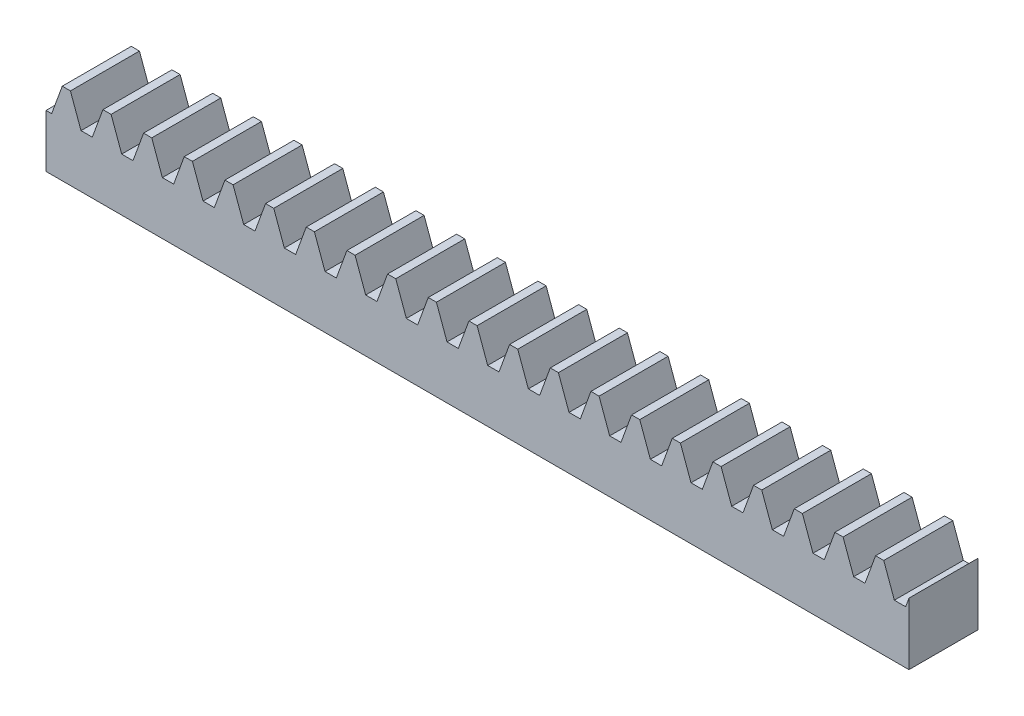
SolidWorks part; units mm, degrees
extrude "Blank" add sketch "BlankSke" against normal blind 8
sketch "BlankSke" plane through (0, 0, 0) normal (0, 0, 1) x (1, 0, 0)
  line L1 (0, 0) -> (100, 0)
  line L2 (0, 0) -> (0, 9.5)
  line L3 (0, 9.5) -> (100, 9.5)
  line L4 (100, 0) -> (100, 9.5)
  dimension "Length" = 100
  dimension "Blank_height" = 9.5
material "ABS PC"
ref_plane "Plane1" through (0, 0, 0) normal (0, 0, 1) x (1, 0, 0)
ref_plane "Plane2" through (0, 0, 0) normal (0, 1, 0) x (1, 0, 0)
ref_plane "Plane3" through (0, 0, 0) normal (1, 0, 0) x (0, 0, -1)
sketch "HoldingSke" plane through (0, 0, 0) normal (0, 1, 0) x (1, 0, 0)
  line L0 (0, 0) -> (0.0928, 0.6602)
  line L1 (-15, 0) -> (100, 0) construction
  line L2 (0, 0) -> (-2.1039, 2.3779)
  line L3 (0, 0) -> (-11.863, 4.5341)
  line L4 (0, 0) -> (7.9495, 3.3743)
  line L5 (0, 0) -> (-23.7986, -8.8762)
  line L6 (0, 0) -> (-10.5278, -7.1032)
  line L9 (-71.009, 38.7566) -> (22.9603, 72.9586)
  line L10 (-76.2, 3.8779) -> (-68.2, 3.8779)
  line L11 (0, 0) -> (-8, 0)
  line L12 (-76.2, 101.6) -> (-76.147, 101.6)
  line L13 (24.9733, 27.94) -> (52.9518, 28.4284)
  line L14 (24.9733, 27.94) -> (24.9743, 27.94)
  line L15 (24.9733, 27.94) -> (100.4006, 29.5858)
  circle A0 centre (0, 0) radius 19.05
  circle A1 centre (0, 0) radius 4
  circle A2 centre (0, 0) radius 12.7
  dimension "MPH" = 8
  dimension "Diameter" = 38.1
  dimension "Num_teeth" = 23
  dimension "Pitch" = 0.6667
  dimension "Show_teeth" = 998
  dimension "Thickness" = 12.7
  dimension "Ap" = 20
  dimension "Pitch_height" = 8
  dimension "Width" = 8
  dimension "Backlash" = 0.053
  dimension "Addendum_fac" = 1
  dimension "Dedendum_fac" = 1.25
  dimension "Clearance_fac" = 0.25
  dimension "Dedendum_add" = 0.001
  dimension "Length" = 100
  dimension "Module" = 1.5
sketch "TooCutSkeIll" plane through (0, 0, 0) normal (0, 0, 1) x (1, 0, 0)
  line L0 (-1.8687, 9.4605) -> (-0.7447, 6.3724)
  line L1 (-0.3914, 6.125) -> (0.3914, 6.125)
  line L2 (0.7447, 6.3724) -> (1.8687, 9.4605)
  line L3 (100, 9.5) -> (0, 9.5) construction
  line L4 (0, 0) -> (0, 64.897) construction
  line L5 (-13.208, 8) -> (12.954, 8) construction
  line L6 (0, 0) -> (100, 0) construction
  line L7 (1.3371, 8) -> (1.3371, 48.7463) construction
  line L8 (-1.3371, 8) -> (-1.3371, 48.7463) construction
  line L9 (1.9251, 9.5) -> (1.9251, 9.5254)
  line L10 (-1.9251, 9.5) -> (-1.9251, 9.5254)
  line L11 (-1.9251, 9.5254) -> (1.9251, 9.5254)
  arc A0 (0.3914, 6.125) -> (0.7447, 6.3724) centre (0.3914, 6.501) ccw
  arc A1 (-0.7447, 6.3724) -> (-0.3914, 6.125) centre (-0.3914, 6.501) ccw
  arc A2 (1.9251, 9.5) -> (1.8687, 9.4605) centre (1.9251, 9.44) ccw
  arc A3 (-1.8687, 9.4605) -> (-1.9251, 9.5) centre (-1.9251, 9.44) ccw
  dimension "Pitch_height" = 8
  dimension "Addendum_plus" = 1.5254
  dimension "Pressure_angle" = 20
  dimension "Gap_width" = 2.6742
  dimension "Dedendum" = 1.875
extrude "ToothCutIll" [suppressed] cut sketch "TooCutSkeIll" against normal through all
sketch "TooCutSkeSim" plane through (0, 0, 0) normal (0, 0, 1) x (1, 0, 0)
  line L0 (0.6547, 6.125) -> (-0.6547, 6.125)
  line L1 (1.8923, 9.5254) -> (0.6547, 6.125)
  line L2 (0, 17.4625) -> (0, 53.467) construction
  line L3 (1.8923, 9.5254) -> (-1.8923, 9.5254)
  line L6 (-1.8923, 9.5254) -> (-0.6547, 6.125)
  line L9 (-1.3371, 8) -> (1.3371, 8) construction
  line L10 (0, 0) -> (100, 0) construction
  line L11 (1.3371, 8) -> (1.3371, 53.467) construction
  line L12 (-1.3371, 8) -> (-1.3371, 53.467) construction
  dimension "Pitch_height" = 8
  dimension "Addendum_plus" = 1.5254
  dimension "Pressure_angle" = 20
  dimension "Gap_width" = 2.6742
  dimension "Dedendum" = 1.875
extrude "ToothCutSim" cut sketch "TooCutSkeSim" against normal through all
pattern_linear "TeethCuts" count 22 spacing 4.7124 along (1, 0, 0) of "ToothCutIll", "ToothCutSim"
sketch "Sketch1" plane through (0, 0, 0) normal (0, -1, 0) x (-1, 0, 0)
  line L0 (-100, 0) -> (45.4658, 0) construction
sketch "Sketch2" plane through (0, 0, 0) normal (0, -1, 0) x (1, 0, 0)
  line L0 (0, -8) -> (118.446, -8) construction
equation "' \"Module@HoldingSke\" = 6.35"
equation "' \"Num_teeth@HoldingSke\" = 12"
equation "' \"Ap@HoldingSke\" =  20"
equation "' \"Ap@HoldingSke\" = 20"
equation "' \"Width@HoldingSke\" = 0.25 * 25.4"
equation "' \"Show_teeth@HoldingSke\" = 500"
equation "' \"Backlash@HoldingSke\" = 0.009 * 25.4"
equation "' \"Addendum_fac@HoldingSke\" = 1.0"
equation "' \"Dedendum_fac@HoldingSke\" = 1.25"
equation "' \"Dedendum_add@HoldingSke\" = 0.00005 * 25.4"
equation "' \"Clearance_fac@HoldingSke\" = 0.25"
equation "' \"Pitch_height@HoldingSke\" = 1 * 25.4"
equation "' \"Length@HoldingSke\" = 4.71 * 25.4"
equation "\"Pitch@HoldingSke\" = 1 / \"Module@HoldingSke\""
equation "\"MPH@HoldingSke\" = \"Dedendum_fac@HoldingSke\" / \"Pitch@HoldingSke\" + 2 * \"Dedendum_add@HoldingSke\" + 0.002 * 25.4"
equation "\"MPH@HoldingSke\" = ((sgn( \"MPH@HoldingSke\" - \"Pitch_height@HoldingSke\")+1)*( \"MPH@HoldingSke\" - \"Pitch_height@HoldingSke\"))/2 + \"Pitch_height@HoldingSke\""
equation "\"Blank_height@BlankSke\" = \"Pitch_height@HoldingSke\" + \"Addendum_fac@HoldingSke\"  / \"Pitch@HoldingSke\" "
equation "\"Length@BlankSke\" =  \"Length@HoldingSke\""
equation "\"Face_width@Blank\" = \"Width@HoldingSke\""
equation "\"Pressure_angle@TooCutSkeIll\" = \"Ap@HoldingSke\""
equation "\"Addendum_plus@TooCutSkeIll\" =  \"Addendum_fac@HoldingSke\"  / \"Pitch@HoldingSke\" + 0.001 *25.4"
equation "\"Dedendum@TooCutSkeIll\" = \"Dedendum_fac@HoldingSke\"  / \"Pitch@HoldingSke\""
equation "\"Pitch_height@TooCutSkeIll\" =  \"MPH@HoldingSke\""
equation "\"Gap_width@TooCutSkeIll\" = 3.14159265 / 2 / \"Pitch@HoldingSke\" + 6 * \"Backlash@HoldingSke\""
equation "\"Pressure_angle@TooCutSkeSim\" = \"Ap@HoldingSke\""
equation "\"Addendum_plus@TooCutSkeSim\" =  \"Addendum_fac@HoldingSke\"  / \"Pitch@HoldingSke\" + 0.001 * 25.4"
equation "\"Dedendum@TooCutSkeSim\" = \"Dedendum_fac@HoldingSke\"  / \"Pitch@HoldingSke\""
equation "\"Pitch_height@TooCutSkeSim\" =  \"MPH@HoldingSke\""
equation "\"Gap_width@TooCutSkeSim\" = 3.14159265 / 2 / \"Pitch@HoldingSke\" + 6 * \"Backlash@HoldingSke\""
equation "\"Root_fillet@TooCutSkeIll\" = \"Clearance_fac@HoldingSke\" / \"Pitch@HoldingSke\" + \"Dedendum_add@HoldingSke\""
equation "\"Break_rad@TooCutSkeIll\" = 0.02 / \"Pitch@HoldingSke\" * 2"
equation "\"Linear_pitch@TeethCuts\" = 3.14159265 / \"Pitch@HoldingSke\""
equation "\"Num_teeth@HoldingSke\" = int( ( \"Length@HoldingSke\" + 0 ) / (3.14159265 / \"Pitch@HoldingSke\")) + 0.9999  + 1"
equation " \"Num_teeth@TeethCuts\" = int( \"Show_teeth@HoldingSke\" ) + 1"
equation " \"Num_teeth@TeethCuts\" = ((sgn( \"Num_teeth@TeethCuts\" - \"Num_teeth@HoldingSke\" )-1)*( \"Num_teeth@TeethCuts\" - \"Num_teeth@HoldingSke\" ))/-2+ \"Num_teeth@HoldingSke\""
equation " \"Num_teeth@TeethCuts\" = ((sgn( \"Num_teeth@TeethCuts\" - 2.0)+1)*( \"Num_teeth@TeethCuts\" - 2.0))/2 +2.0"
